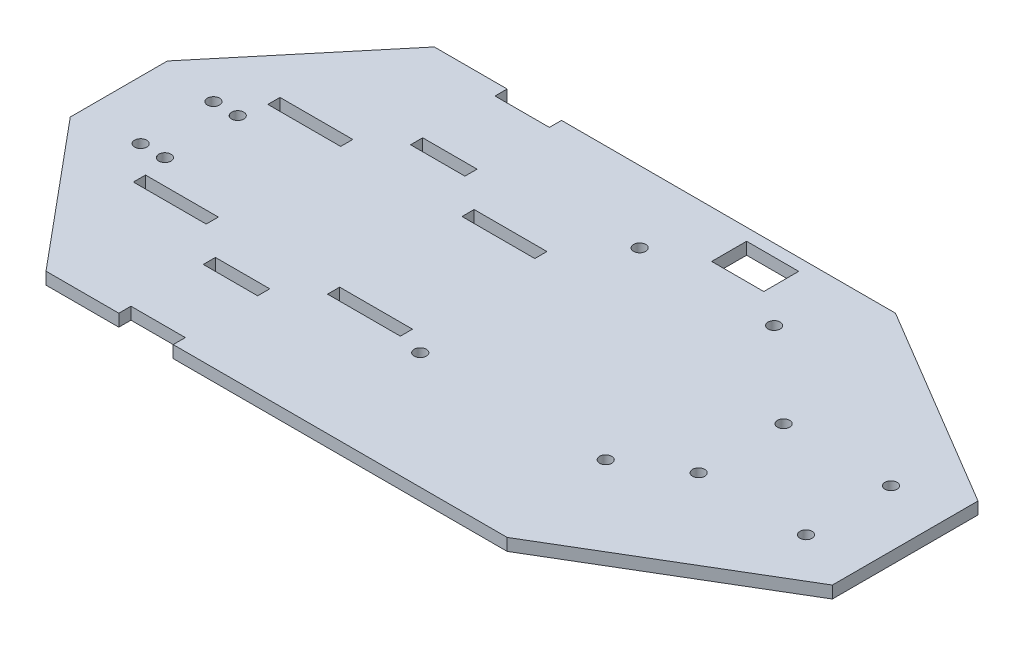
SolidWorks part; units mm, degrees
ref_plane "Front" through (0, 0, 0) normal (0, 0, 1) x (1, 0, 0)
ref_plane "Top" through (0, 0, 0) normal (0, 1, 0) x (1, 0, 0)
ref_plane "Right" through (0, 0, 0) normal (1, 0, 0) x (0, 0, -1)
sketch "Sketch1" plane through (0, 0, 0) normal (0, 1, 0) x (1, 0, 0)
  line L0 (0, 50.8) -> (228.6, 50.8) construction
  line L1 (0, 0) -> (228.6, 0)
  line L2 (0, 0) -> (0, 101.6)
  line L3 (0, 101.6) -> (228.6, 101.6)
  line L4 (228.6, 0) -> (228.6, 101.6)
  line L5 (50.8, 0) -> (65.024, 0)
  line L6 (50.8, 0) -> (50.8, 3.175)
  line L7 (50.8, 3.175) -> (65.024, 3.175)
  line L8 (65.024, 0) -> (65.024, 3.175)
  line L9 (50.8, 22.098) -> (65.024, 22.098)
  line L10 (50.8, 22.098) -> (50.8, 25.273)
  line L11 (50.8, 25.273) -> (65.024, 25.273)
  line L12 (65.024, 22.098) -> (65.024, 25.273)
  line L13 (96.774, 85.09) -> (150.114, 85.09) construction
  line L14 (96.774, 85.09) -> (96.774, 16.51) construction
  line L15 (96.774, 16.51) -> (150.114, 16.51) construction
  line L16 (150.114, 85.09) -> (150.114, 16.51) construction
  line L18 (162.814, 61.9125) -> (162.814, 39.6875) construction
  line L19 (116.6241, 98.425) -> (130.2639, 98.425)
  line L20 (116.6241, 98.425) -> (116.6241, 89.281)
  line L21 (116.6241, 89.281) -> (130.2639, 89.281)
  line L22 (130.2639, 98.425) -> (130.2639, 89.281)
  line L23 (50.8, 98.425) -> (65.024, 98.425)
  line L24 (65.024, 101.6) -> (65.024, 98.425)
  line L25 (50.8, 101.6) -> (65.024, 101.6)
  line L26 (50.8, 101.6) -> (50.8, 98.425)
  line L27 (50.8, 76.327) -> (65.024, 76.327)
  line L28 (65.024, 79.502) -> (65.024, 76.327)
  line L29 (50.8, 79.502) -> (65.024, 79.502)
  line L30 (50.8, 79.502) -> (50.8, 76.327)
  line L31 (42.037, 69.977) -> (73.787, 69.977) construction
  line L32 (22.987, 69.977) -> (42.037, 69.977)
  line L33 (22.987, 69.977) -> (22.987, 66.802)
  line L34 (22.987, 66.802) -> (42.037, 66.802)
  line L35 (42.037, 69.977) -> (42.037, 66.802)
  line L36 (73.787, 69.977) -> (92.837, 69.977)
  line L37 (73.787, 69.977) -> (73.787, 66.802)
  line L38 (73.787, 66.802) -> (92.837, 66.802)
  line L39 (92.837, 69.977) -> (92.837, 66.802)
  line L40 (73.787, 34.798) -> (92.837, 34.798)
  line L41 (92.837, 31.623) -> (92.837, 34.798)
  line L42 (73.787, 31.623) -> (92.837, 31.623)
  line L43 (73.787, 31.623) -> (73.787, 34.798)
  line L44 (22.987, 34.798) -> (42.037, 34.798)
  line L45 (42.037, 31.623) -> (42.037, 34.798)
  line L46 (22.987, 31.623) -> (42.037, 31.623)
  line L47 (22.987, 31.623) -> (22.987, 34.798)
  circle A0 centre (99.187, 30.48) radius 1.5875
  circle A1 centre (147.701, 30.48) radius 1.5875
  circle A2 centre (162.814, 61.9125) radius 1.5875
  circle A3 centre (162.814, 39.6875) radius 1.5875
  circle A4 centre (190.9128, 61.9125) radius 1.5875
  circle A5 centre (190.9128, 39.6875) radius 1.5875
  circle A6 centre (104.14, 82.931) radius 1.5875
  circle A7 centre (139.319, 82.931) radius 1.5875
  point P15 (150.114, 50.8)
  point P20 (228.6, 50.8)
  point P27 (162.814, 50.8)
  point P36 (123.444, 85.09)
  point P37 (123.444, 98.425)
  point P56 (57.912, 69.977)
  point P57 (57.912, 76.327)
  dimension "D11" = 3.175
  dimension "D17" = 3.175
  dimension "D1" = 101.6
  dimension "D2" = 228.6
  dimension "D3" = 14.224
  dimension "D4" = 3.175
  dimension "D5" = 18.923
  dimension "D6" = 31.75
  dimension "D7" = 68.58
  dimension "D8" = 53.34
  dimension "D9" = 50.8
  dimension "D10" = 2.413
  dimension "D12" = 13.97
  dimension "D13" = 13.97
  dimension "D14" = 2.413
  dimension "D15" = 12.7
  dimension "D16" = 22.225
  dimension "D18" = 28.0987
  dimension "D19" = 9.144
  dimension "D20" = 13.6398
  dimension "D21" = 3.175
  dimension "D22" = 19.05
  dimension "D23" = 31.75
  dimension "D24" = 3.175
  dimension "D25" = 6.35
  dimension "D26" = 2.159
  dimension "D27" = 7.366
  dimension "D28" = 35.179
extrude "Boss-Extrude1" add sketch "Sketch1" along normal blind 3.175 contours L26 L3 L2 L1 L6 L7 L8 L4 L24 L23 A5 A4 A3 A2 A1 A0 L30 L29 L28 L27 L12 L9 L10 L11 L19 L22 L21 L20 L32 L35 L34 L33 L36 L39 L38 L37 L42
sketch "Sketch2" plane through (0, 3.175, 0) normal (0, 1, 0) x (1, 0, 0)
  line L0 (15.24, 60.325) -> (15.24, 41.275) construction
  line L1 (0, 0) -> (0, 101.6) construction
  circle A0 centre (15.24, 60.325) radius 1.5875
  circle A1 centre (15.24, 41.275) radius 1.5875
  circle A2 centre (21.59, 41.275) radius 1.5875
  circle A3 centre (21.59, 60.325) radius 1.5875
  point P10 (0, 50.8)
  point P11 (15.24, 50.8)
  dimension "D1" = 3.175
  dimension "D2" = 19.05
  dimension "D3" = 6.35
  dimension "D4" = 15.24
extrude "Cut-Extrude1" cut sketch "Sketch2" against normal up to surface (3.175 mm away) up to face at (139.319, 0, -81.3435)
sketch "Sketch3" plane through (0, 3.175, 0) normal (0, 1, 0) x (1, 0, 0)
  line L0 (0, 63.5) -> (31.75, 101.6)
  line L1 (0, 0) -> (0, 101.6) construction
  line L2 (0, 101.6) -> (50.8, 101.6) construction
  line L3 (31.75, 101.6) -> (0, 101.6)
  line L4 (0, 101.6) -> (0, 63.5)
  line L5 (152.4, 101.6) -> (205.74, 69.85)
  line L6 (65.024, 101.6) -> (228.6, 101.6) construction
  line L7 (228.6, 0) -> (228.6, 101.6) construction
  line L8 (228.6, 57.15) -> (228.6, 101.6)
  line L9 (228.6, 101.6) -> (152.4, 101.6)
  line L11 (228.6, 0) -> (152.4, 0)
  line L16 (228.6, 44.45) -> (228.6, 0)
  line L18 (0, 50.8) -> (228.6, 50.8) construction
  line L19 (152.4, 0) -> (205.74, 31.75)
  line L20 (31.75, 0) -> (0, 0)
  line L21 (0, 38.1) -> (31.75, 0)
  line L22 (0, 0) -> (0, 38.1)
  line L23 (205.74, 69.85) -> (205.74, 31.75)
  line L24 (228.6, 57.15) -> (228.6, 44.45)
  point P26 (205.74, 50.8)
  dimension "D1" = 38.1
  dimension "D2" = 31.75
  dimension "D3" = 76.2
  dimension "D4" = 44.45
  dimension "D5" = 22.86
  dimension "D6" = 19.05
extrude "Cut-Extrude2" cut sketch "Sketch3" against normal through all
